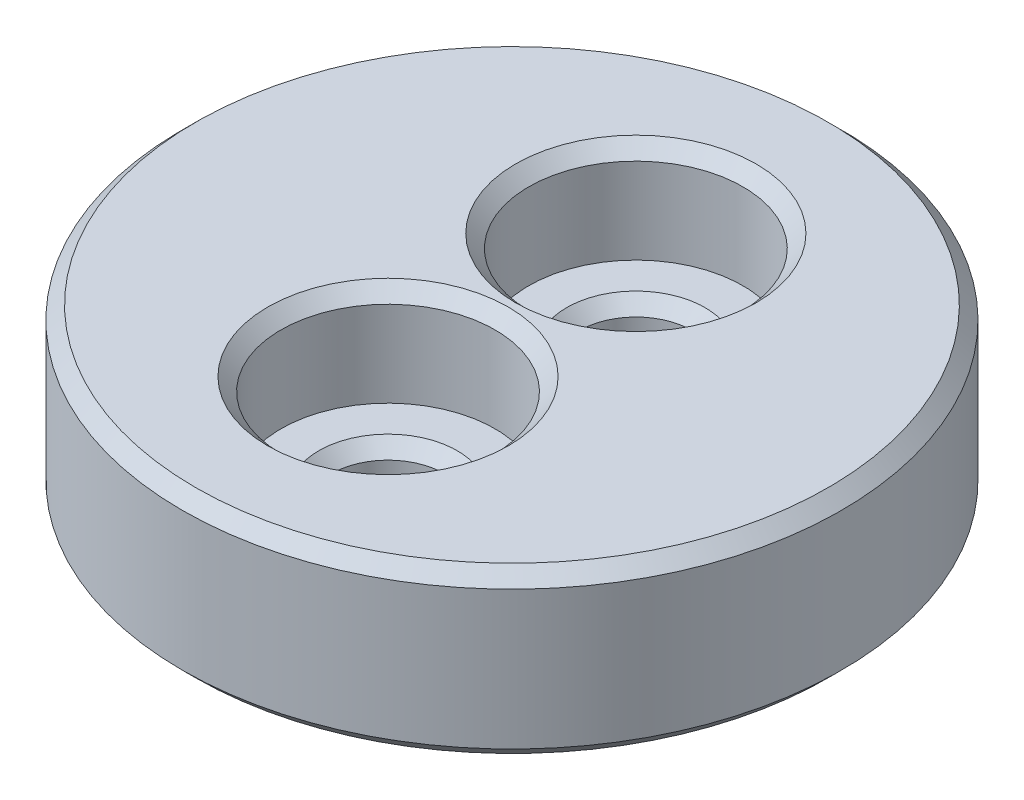
SolidWorks part; units mm, degrees
ref_plane "Front Plane" through (0, 0, 0) normal (0, 0, 1) x (1, 0, 0)
ref_plane "Top Plane" through (0, 0, 0) normal (0, 1, 0) x (1, 0, 0)
ref_plane "Right Plane" through (0, 0, 0) normal (1, 0, 0) x (0, 0, -1)
sketch "Sketch1" plane through (0, 0, 0) normal (0, 1, 0) x (1, 0, 0)
  line L0 (0, 3.76) -> (0, -3.76) construction
  circle A0 centre (0, 0) radius 10
  point P5 (0, 0)
  dimension "D1" = 20
  dimension "D2" = 7.52
extrude "Boss-Extrude1" add sketch "Sketch1" along normal blind 5
hole_wizard "CBORE for M3 SHCS1" positions "Sketch2" profile "Sketch3" counterbore size "M3" standard "ANSI Metric" end condition through all
sketch "Sketch2" plane through (0, 5, 0) normal (0, 1, 0) x (1, 0, 0)
  point P0 (0, 3.76)
  point P3 (0, -3.76)
sketch "Sketch3" plane through (0, 5, -3.76) normal (1, 0, 0) x (0, 0, 1)
  line L0 (0, 0) -> (0, 5)
  line L1 (1.7, 4.6) -> (2.1, 5)
  line L2 (1.7, 4.6) -> (1.7, 3.4)
  line L3 (1.7, 3.4) -> (2.1, 3)
  line L4 (2.1, 3) -> (3.25, 3)
  line L5 (3.25, 3) -> (3.25, 0.4)
  line L6 (3.25, 0.4) -> (3.65, 0)
  line L7 (3.65, 0) -> (0, 0)
  line L8 (-3.25, 0.4) -> (-3.65, 0) construction
  line L9 (-1.7, 3.4) -> (-2.1, 3) construction
  line L11 (0, -6.35) -> (0, 107.95) construction
  line L12 (2.1, 5) -> (0, 5)
  line L13 (-1.7, 4.6) -> (-2.1, 5) construction
  dimension "Thru Hole Dia." = 3.4
  dimension "Thru Hole Depth" = 5
  dimension "C'Bore Dia." = 6.5
  dimension "C'Bore Depth" = 3
  dimension "Near C'Sink Dia." = 7.3
  dimension "Near C'Sink Angle" = 90
  dimension "Mid C'Sink Dia." = 4.2
  dimension "Mid C'Sink Angle" = 90
  dimension "Far C'Sink Dia." = 4.2
  dimension "Far C'Sink Angle" = 90
chamfer "Chamfer1" distance 0.4 angle 45 2 edges at (0, 0, 10) (0, 5, 10)
